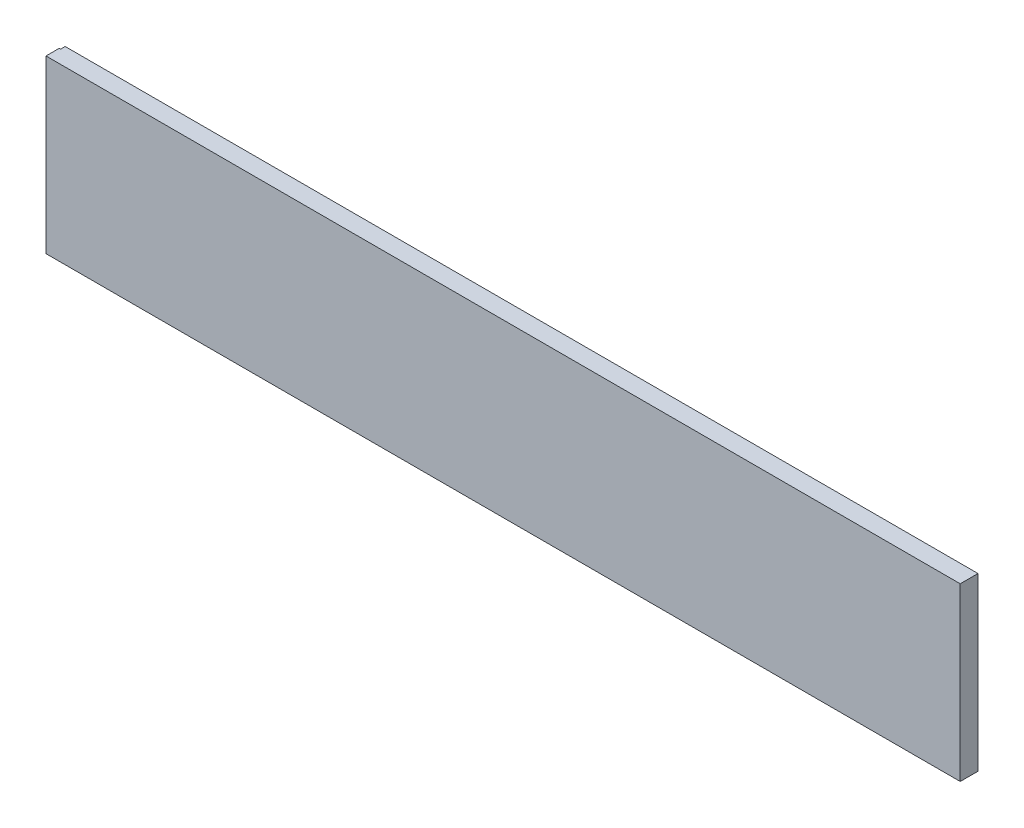
SolidWorks part; units mm, degrees
ref_plane "Front Plane" through (0, 0, 0) normal (0, 0, 1) x (1, 0, 0)
ref_plane "Top Plane" through (0, 0, 0) normal (0, 1, 0) x (1, 0, 0)
ref_plane "Right Plane" through (0, 0, 0) normal (1, 0, 0) x (0, 0, -1)
sketch "Sketch1" plane through (0, 0, 0) normal (0, 0, 1) x (1, 0, 0)
  line L0 (0, 0) -> (0, 152.64) construction
  line L1 (-406.4, -152.64) -> (406.4, -152.64)
  line L2 (-406.4, -152.64) -> (-406.4, 152.64)
  line L5 (-406.4, -152.64) -> (406.4, 152.64) construction
  line L6 (-406.4, 152.64) -> (406.4, -152.64) construction
  line L7 (0, 152.64) -> (0, 95.04)
  line L8 (0, 0) -> (406.4, 0) construction
  line L9 (-406.4, 152.64) -> (-406.4, 232.64)
  line L10 (-406.4, 232.64) -> (1650.5081, 232.64)
  line L11 (406.4, -152.64) -> (1650.5081, -152.64)
  line L12 (1650.5081, -152.64) -> (1650.5081, 232.64)
  circle A0 centre (0, 0) radius 36
  circle A1 centre (0, 95.04) radius 20.52
  circle A2 centre (0, -95.04) radius 20.52
  point P0 (0, 0)
extrude "Boss-Extrude1" add sketch "Sketch1" along normal blind 20
sketch "Sketch2" plane through (0, 0, 20) normal (0, 0, 1) x (1, 0, 0)
  line L0 (-406.4, 232.64) -> (-406.4, -152.64)
  line L1 (-406.4, -152.64) -> (1650.5081, -152.64)
  line L2 (1650.5081, -152.64) -> (1650.5081, 232.64)
  line L3 (1650.5081, 232.64) -> (-406.4, 232.64)
extrude "Boss-Extrude2" add sketch "Sketch2" along normal blind 10
sketch "Sketch3" plane through (0, 0, 20) normal (0, 0, -1) x (-1, 0, 0)
  circle A0 centre (0, 0) radius 36
extrude "Boss-Extrude3" add sketch "Sketch3" along normal blind 30
sketch "Sketch4" plane through (0, 0, 0) normal (0, 0, -1) x (-1, 0, 0)
  line L0 (-1650.5081, 232.64) -> (-1650.5081, -152.64)
  line L1 (-1650.5081, 232.64) -> (403.2337, 232.64)
  line L2 (-1650.5081, -152.64) -> (403.2337, -152.64)
  line L3 (403.2337, 232.64) -> (403.2337, -152.64)
  line L4 (406.4, -152.64) -> (-1650.5081, -152.64) construction
  line L5 (-1650.5081, -152.64) -> (-1650.5081, 232.64) construction
  line L6 (-1650.5081, 232.64) -> (-1630.5081, 232.64)
  line L7 (-1630.5081, 212.64) -> (-1630.5081, -143.7511)
  line L8 (-1630.5081, -143.7511) -> (-1630.5081, -132.64)
  line L9 (-1630.5081, -132.64) -> (382.5348, -132.64)
  line L11 (382.5348, -132.64) -> (382.5348, 212.64)
  line L13 (382.5348, 212.64) -> (-1630.5081, 212.64)
extrude "Boss-Extrude4" add sketch "Sketch4" along normal blind 10
